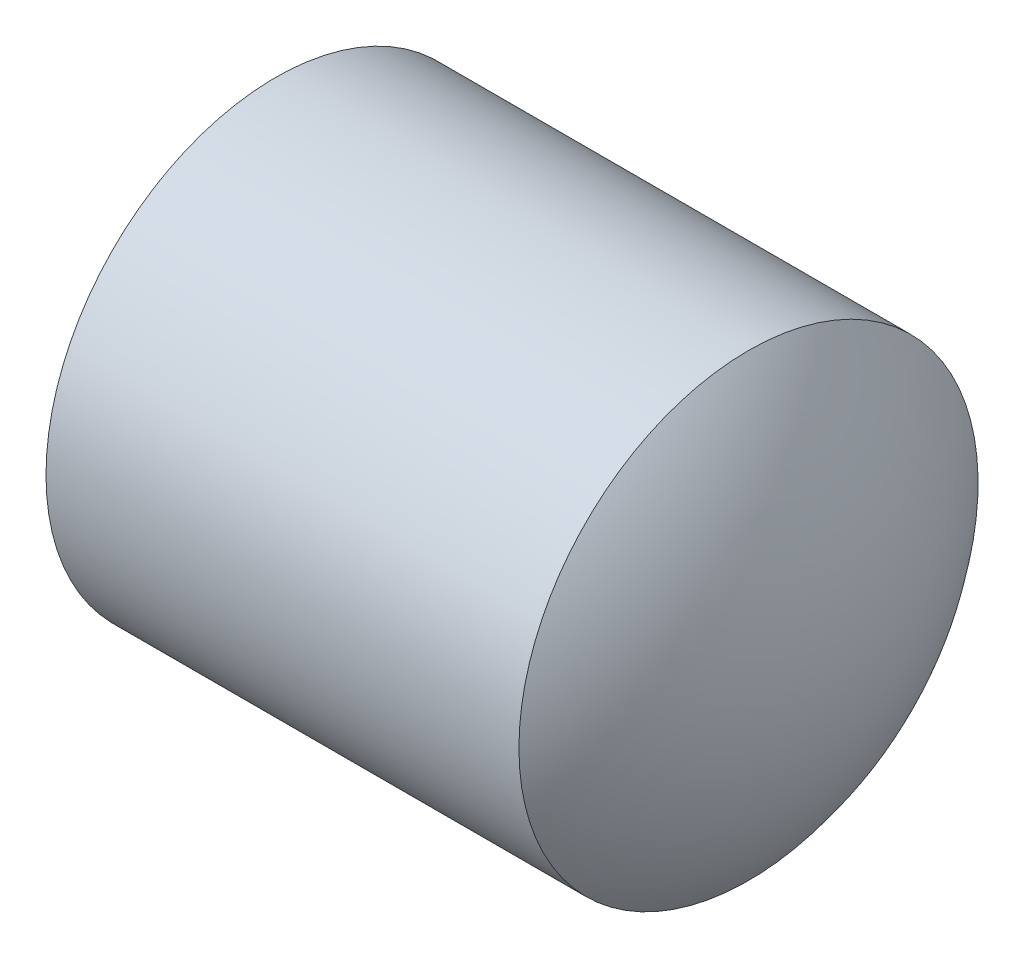
SolidWorks part; units mm, degrees
revolve "BaseBody" add sketch "BodySke" angle 360 about L5
sketch "BodySke" plane through (0, 0, 0) normal (0, 0, 1) x (1, 0, 0)
  line L0 (0, 0) -> (0, 10.352)
  line L1 (0, 10.352) -> (0.9515, 12)
  line L2 (0.9515, 12) -> (25.672, 12)
  line L3 (3, 15.875) -> (3, -3.175) construction
  line L4 (30, 0) -> (0, 0)
  line L5 (-12.7, 0) -> (88.9, 0) construction
  line L8 (0, -10.352) -> (0.9515, -12) construction
  arc A0 (30, 0) -> (25.672, 12) centre (11.2, 0) ccw
  dimension "Oval_radius" = 18.8
  dimension "Diameter" = 24
  dimension "Drive_ch_ang" = 60
  dimension "Minor_dia" = 20.704
  dimension "Length" = 30
  dimension "Advance" = 3
cosmetic thread "ThreadCosmetic" [suppressed] parameters "Thread_minor"=20.704
ref_plane "Plane1" through (0, 0, 0) normal (0, 0, 1) x (1, 0, 0)
ref_plane "Plane2" through (0, 0, 0) normal (0, 1, 0) x (1, 0, 0)
ref_plane "Plane3" through (0, 0, 0) normal (1, 0, 0) x (0, 0, -1)
sketch "Sketch2" plane through (0, 0, 0) normal (-1, 0, 0) x (0, 0, 1)
  line L0 (3.4641, 6) -> (-3.4641, 6)
  line L1 (-3.4641, 6) -> (-6.9282, 0)
  line L2 (3.4641, 6) -> (6.9282, 0)
  line L3 (3.4641, -6) -> (6.9282, 0)
  line L4 (3.4641, -6) -> (-3.4641, -6)
  line L5 (-3.4641, -6) -> (-6.9282, 0)
  dimension "Hex_size" = 12
  dimension "D2" = 6
  dimension "D3" = 6
extrude "Hex" cut sketch "Sketch2" against normal blind 12
sketch "Sketch4" plane through (0, 4.7709, -0.5249) normal (-1, 0, 0) x (0, 0, 1)
  line L0 (0.5249, -4.7709) -> (10.6976, -4.7709)
  line L1 (0.5249, -4.7709) -> (6.6732, -1.2211) construction
  line L2 (0.5249, -4.7709) -> (5.6112, 4.0389)
  line L3 (8.9666, -2.6687) -> (10.2861, -1.9069)
  line L4 (6.5663, 1.4888) -> (7.8858, 2.2506)
  arc A0 (8.9666, -2.6687) -> (6.5663, 1.4888) centre (0.5249, -4.7709) ccw
  arc A1 (10.6976, -4.7709) -> (10.2861, -1.9069) centre (0.5249, -4.7709) ccw
  arc A2 (5.6112, 4.0389) -> (7.8858, 2.2506) centre (0.5249, -4.7709) cw
  circle A3 centre (0.5249, -4.7709) radius 8.6995 construction
  circle A4 centre (0.5249, -4.7709) radius 10.1727 construction
  dimension "Spline_n_dim" = 17.399
  dimension "Spline_m_dim" = 20.3454
  dimension "D1" = 30
  dimension "Spline_a_dim" = 60
  dimension "Spline_p_dim" = 4.8006
  dimension "D3" = 2.4003
extrude "Spline6" [suppressed] cut sketch "Sketch4" against normal blind 12
pattern_circular "CirPattern1" [suppressed] count 6 every 60 about axis through (-12.7, 0, 0) along (1, 0, 0)
sketch "Sketch5" plane through (0, -2.3417, -0.7053) normal (-1, 0, 0) x (0, 0, 1)
  line L0 (0.7053, 2.3417) -> (10.878, 2.3417)
  line L1 (0.7053, 2.3417) -> (5.7254, 7.3618) construction
  line L2 (0.7053, 2.3417) -> (0.7053, 12.5144)
  line L3 (8.554, 6.7959) -> (9.3926, 7.6345)
  line L4 (5.1595, 10.1904) -> (5.9981, 11.029)
  line L5 (5.1595, 10.1904) -> (8.554, 6.7959)
  arc A1 (10.878, 2.3417) -> (9.3926, 7.6345) centre (0.7053, 2.3417) ccw
  arc A2 (0.7053, 12.5144) -> (5.9981, 11.029) centre (0.7053, 2.3417) cw
  circle A3 centre (0.7053, 2.3417) radius 8.6995 construction
  circle A4 centre (0.7053, 2.3417) radius 10.1727 construction
  dimension "Spline_n_dim" = 17.399
  dimension "Spline_m_dim" = 20.3454
  dimension "Spline_p_dim" = 4.8006
  dimension "D3" = 2.4003
  dimension "D1" = 45
  dimension "Spline_a_dim" = 90
extrude "Spline4" [suppressed] cut sketch "Sketch5" against normal blind 12
pattern_circular "CirPattern2" [suppressed] count 4 every 90 about axis through (-12.7, 0, 0) along (1, 0, 0)
sketch "ThdSchSke" plane through (0, 0, 0) normal (0, 0, 1) x (1, 0, 0)
  line L0 (0.9515, -10.352) -> (-0.2025, -12)
  line L1 (0.9515, -10.352) -> (2.1054, -12)
  line L2 (2.1054, -12) -> (2.1054, -15)
  line L3 (-3.175, 0) -> (5.1513, 0) construction
  line L4 (0.9515, 12) -> (0.9515, -12) construction
  line L5 (2.1054, -15) -> (-0.2025, -15)
  line L6 (-0.2025, -15) -> (-0.2025, -12)
  dimension "Thread_minor" = 20.704
  dimension "Diameter" = 24
revolve "ThreadSchematic" [suppressed] cut sketch "ThdSchSke" angle 360 about L3
pattern_linear "ThdSchPat" [suppressed]
equation "\"D2@Sketch2\" = \"Hex_size@Sketch2\" / 2"
equation "\"D3@Sketch2\" = \"Hex_size@Sketch2\" / 2"
equation "\"Thread_minor@ThreadCosmetic\" = \"Minor_dia@BodySke\""
equation "\"D1@Sketch4\" = \"Spline_a_dim@Sketch4\" / 2"
equation "\"D3@Sketch4\" = \"Spline_p_dim@Sketch4\" / 2"
equation "\"D2@CirPattern1\" = \"Spline_a_dim@Sketch4\""
equation "\"Num_teeth@CirPattern1\" = 360 / \"D2@CirPattern1\""
equation "\"Spline_a_dim@Sketch5\" = 90"
equation "\"Spline_p_dim@Sketch5\" = \"Spline_p_dim@Sketch4\""
equation "\"Spline_m_dim@Sketch5\" = \"Spline_m_dim@Sketch4\""
equation "\"Spline_n_dim@Sketch5\" = \"Spline_n_dim@Sketch4\""
equation "\"D1@Sketch5\" = \"Spline_a_dim@Sketch5\" / 2"
equation "\"D3@Sketch5\" = \"Spline_p_dim@Sketch5\" / 2"
equation "\"Key_eng@Spline4\" = \"Key_eng@Spline6\""
equation "\"Thread_minor@ThdSchSke\" = \"Thread_minor@ThreadCosmetic\""
equation "\"Diameter@ThdSchSke\" = \"Diameter@BodySke\""
equation "\"Overcut@ThdSchSke\" = \"Diameter@BodySke\" * 1.25"
equation "\"Num_threads@ThdSchPat\" = int( (\"Length@BodySke\" - ( ( ( \"Diameter@BodySke\" - \"Minor_dia@BodySke\" ) * 0.5 ) / tan( \"Drive_ch_ang@BodySke\" * 0.017453292 ) ) - ( \"Oval_radius@BodySke\" - sqr ( ( \"Oval_radius@BodySke\" * \"Oval_radius@BodySke\" ) - ( ( \"Diameter@BodySke\" * 0.5 ) * ( \"Diameter@BodySke\" * 0.5 ) ) ) ) ) / \"Advance@BodySke\" + 0.999 )  + 1"
equation "\"Advance@ThdSchPat\" = (\"Length@BodySke\" - ( ( ( \"Diameter@BodySke\" - \"Minor_dia@BodySke\" ) * 0.5 ) / tan( \"Drive_ch_ang@BodySke\" * 0.017453292 ) ) - ( \"Oval_radius@BodySke\" - sqr ( ( \"Oval_radius@BodySke\" * \"Oval_radius@BodySke\" ) - ( ( \"Diameter@BodySke\" * 0.5 ) * ( \"Diameter@BodySke\" * 0.5 ) ) ) ) ) /  (\"Num_threads@ThdSchPat\" - 1) 'relax it"
equation "' \"Num_threads@ThdSchPat\" = \"Num_threads@ThdSchPat\" - sgn( \"Num_threads@ThdSchPat\" - 1) '---chamfered tips only---"
